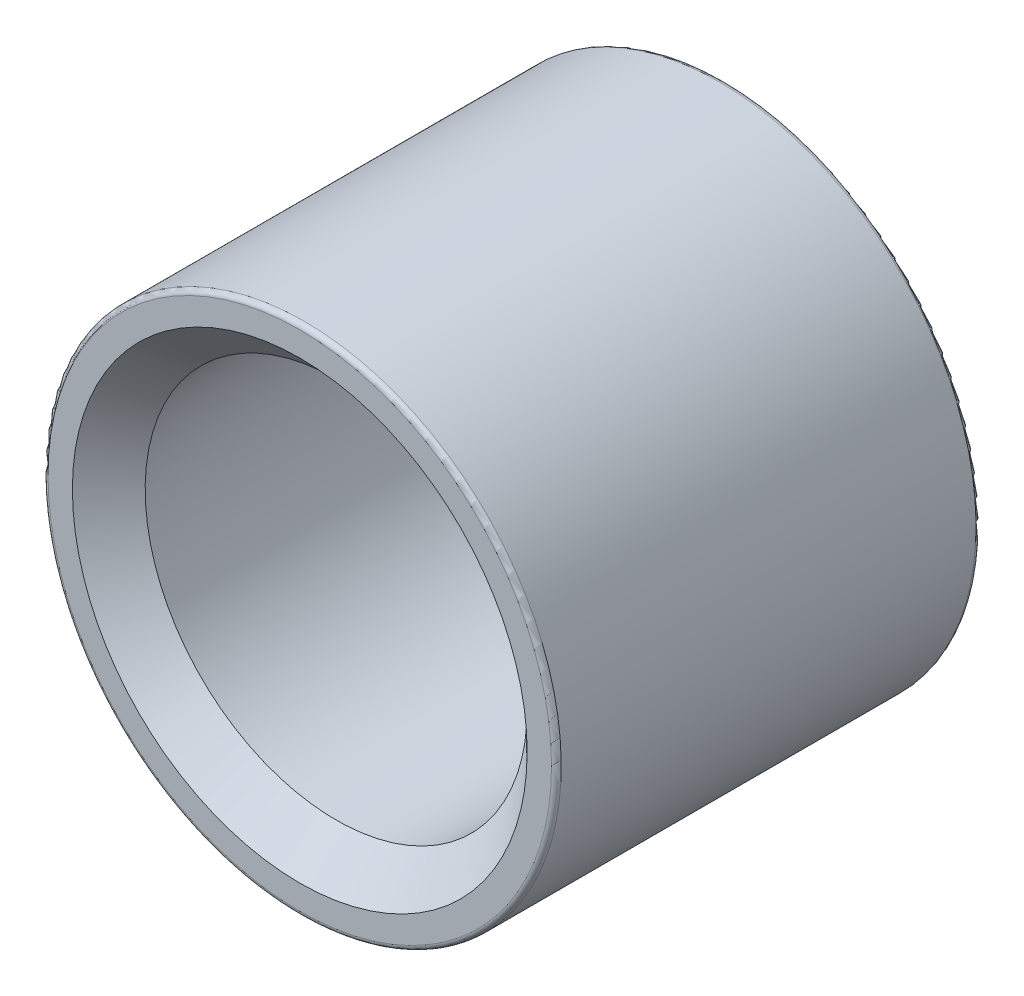
SolidWorks part; units mm, degrees
material "ABS"
ref_plane "Front Plane" through (0, 0, 0) normal (0, 0, 1) x (1, 0, 0)
ref_plane "Top Plane" through (0, 0, 0) normal (0, 1, 0) x (1, 0, 0)
ref_plane "Right Plane" through (0, 0, 0) normal (1, 0, 0) x (0, 0, -1)
sketch "Sketch2" plane through (0, 0, 0) normal (1, 0, 0) x (0, 0, -1)
  line L0 (-14.795, 9.374) -> (-14.795, 10.3791)
  line L1 (-14.595, 10.5791) -> (2.505, 10.5791)
  line L2 (2.705, 10.3791) -> (2.705, 0)
  line L3 (2.705, 0) -> (0, 0)
  line L4 (0, 0) -> (0, 7.874)
  line L5 (0, 7.874) -> (-13.295, 7.874)
  line L6 (-13.295, 7.874) -> (-14.795, 9.374)
  arc A0 (2.505, 10.5791) -> (2.705, 10.3791) centre (2.505, 10.3791) cw
  arc A1 (-14.795, 10.3791) -> (-14.595, 10.5791) centre (-14.595, 10.3791) cw
  point P0 (-14.795, 7.874)
  point P9 (2.705, 10.5791)
  point P12 (-14.795, 10.5791)
  dimension "D6" = 0.2
  dimension "D1" = 10.5791
  dimension "D2" = 7.874
  dimension "D3" = 17.5
  dimension "D4" = 2.705
  dimension "D5" = 2.7051
revolve "Revolve1" add sketch "Sketch2" angle 360 about L3
